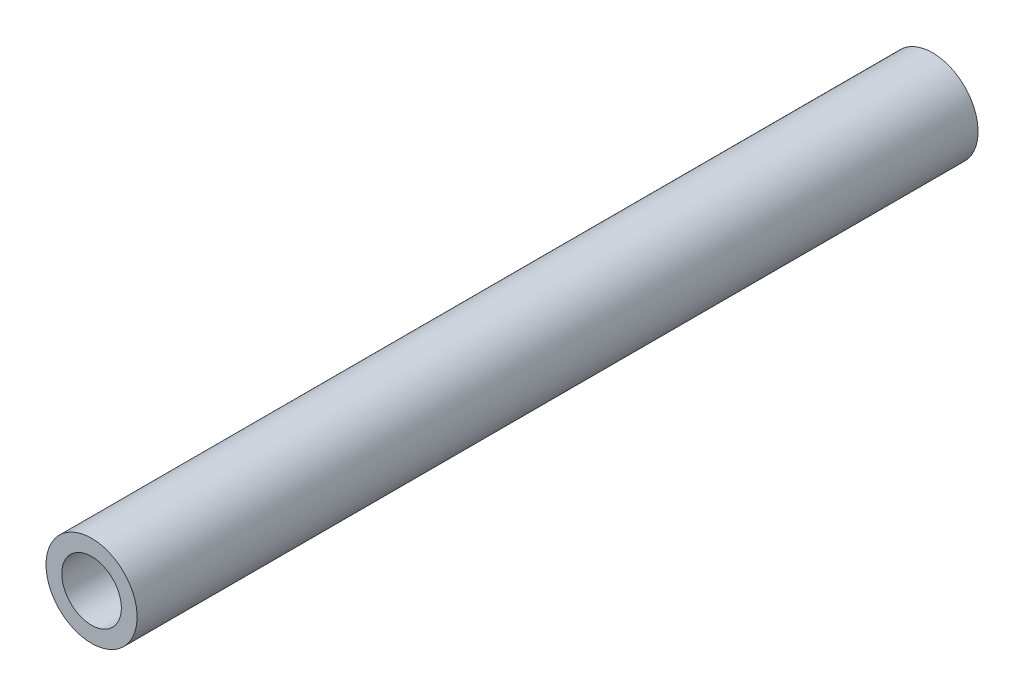
SolidWorks part; units mm, degrees
ref_plane "Front Plane" through (0, 0, 0) normal (0, 0, 1) x (1, 0, 0)
ref_plane "Top Plane" through (0, 0, 0) normal (0, 1, 0) x (1, 0, 0)
ref_plane "Right Plane" through (0, 0, 0) normal (1, 0, 0) x (0, 0, -1)
sketch "Sketch1" plane through (0, 0, 0) normal (0, 0, 1) x (1, 0, 0)
  circle A0 centre (0, 0) radius 16.51
  dimension "D1" = 33.02
extrude "Boss-Extrude1" add sketch "Sketch1" along normal blind 304.8
sketch "Sketch2" plane through (0, 0, 0) normal (0, 0, -1) x (-1, 0, 0)
  circle A0 centre (0, 0) radius 10.795
  dimension "D1" = 21.59
extrude "Cut-Extrude1" cut sketch "Sketch2" against normal through all
